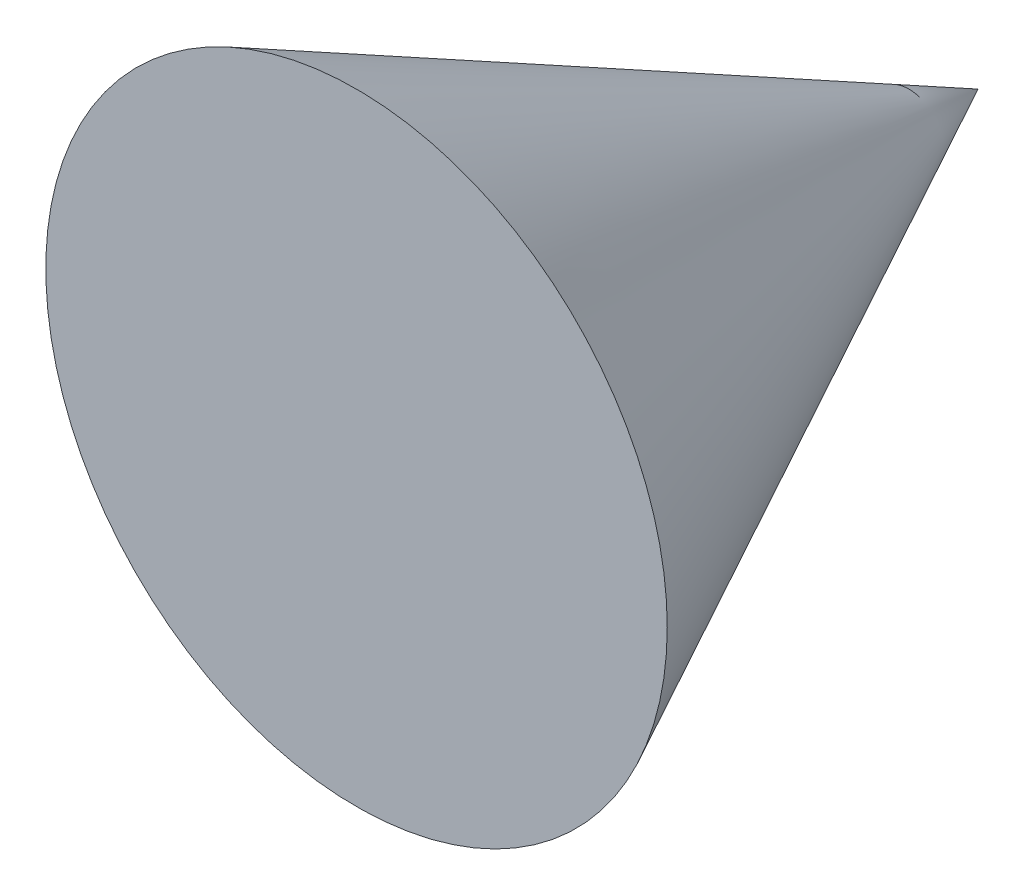
SolidWorks part; units mm, degrees
ref_plane "前视基准面" through (0, 0, 0) normal (0, 0, 1) x (1, 0, 0)
ref_plane "上视基准面" through (0, 0, 0) normal (0, 1, 0) x (1, 0, 0)
ref_plane "右视基准面" through (0, 0, 0) normal (1, 0, 0) x (0, 0, -1)
other "Configuration Table"
sketch "草图1" plane through (0, 0, 0) normal (0, 1, 0) x (1, 0, 0)
  line L0 (0, 0) -> (0, 200) construction
  line L1 (0, 0) -> (100, 0)
  line L2 (100, 0) -> (0, 200)
  line L3 (0, 200) -> (0, 0)
revolve "旋转1" add sketch "草图1" angle 360 about L0
